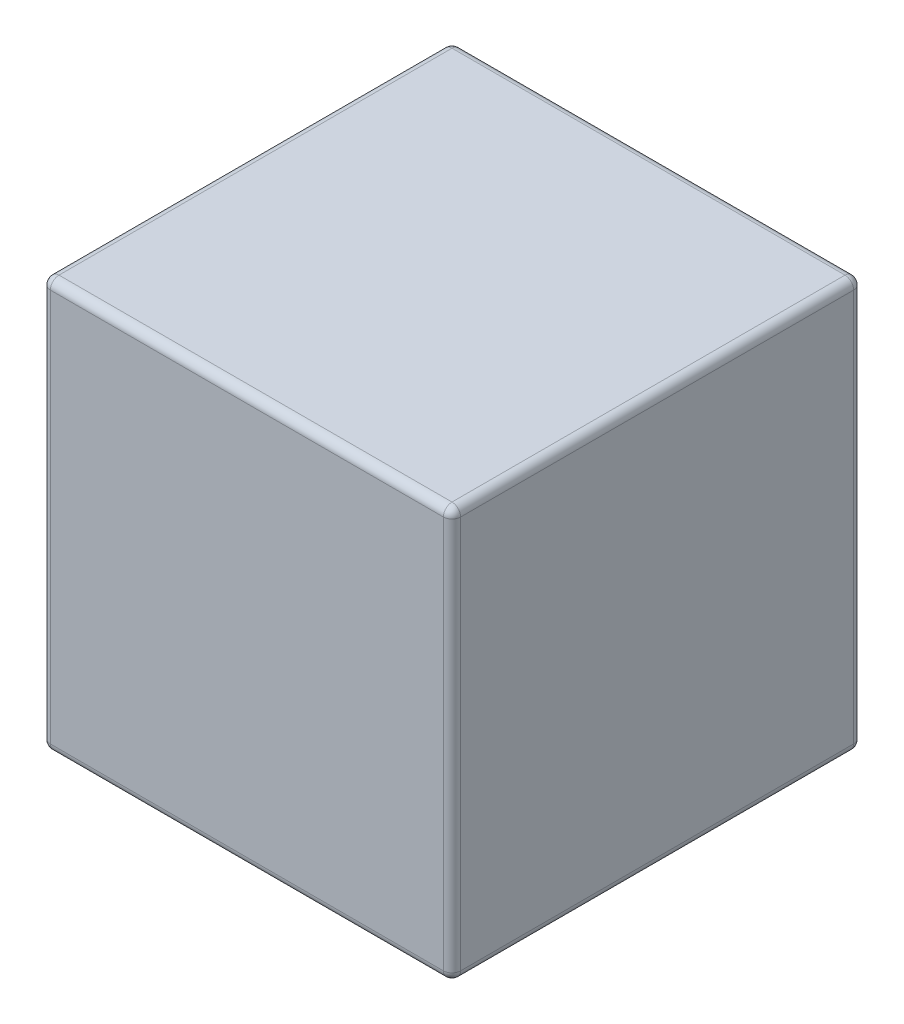
SolidWorks part; units mm, degrees
ref_plane "Front Plane" through (0, 0, 0) normal (0, 0, 1) x (1, 0, 0)
ref_plane "Top Plane" through (0, 0, 0) normal (0, 1, 0) x (1, 0, 0)
ref_plane "Right Plane" through (0, 0, 0) normal (1, 0, 0) x (0, 0, -1)
sketch "Sketch2" plane through (0, 0, 0) normal (0, 1, 0) x (1, 0, 0)
  line L5 (-47.5, -47.5) -> (47.5, -47.5)
  line L6 (-47.5, -47.5) -> (-47.5, 47.5)
  line L7 (-47.5, 47.5) -> (47.5, 47.5)
  line L8 (47.5, -47.5) -> (47.5, 47.5)
  line L9 (-47.5, -47.5) -> (47.5, 47.5) construction
  line L10 (-47.5, 47.5) -> (47.5, -47.5) construction
  point P0 (0, 0)
  dimension "D1" = 95
extrude "Boss-Extrude1" add sketch "Sketch2" along normal blind 95
fillet "Fillet1" radius 2 12 edges at (-47.5, 47.5, 47.5) (47.5, 47.5, 47.5) (-47.5, 0, 0) (0, 0, 47.5) (47.5, 0, 0) (47.5, 47.5, -47.5) (-47.5, 47.5, -47.5) (0, 0, -47.5) (0, 95, 47.5) (-47.5, 95, 0) (0, 95, -47.5) (47.5, 95, 0)
equation "\"magnet_size\"= 95"
equation "\"D1@Sketch2\"=\"magnet_size\""
equation "\"D1@Boss-Extrude1\"=\"magnet_size\""
